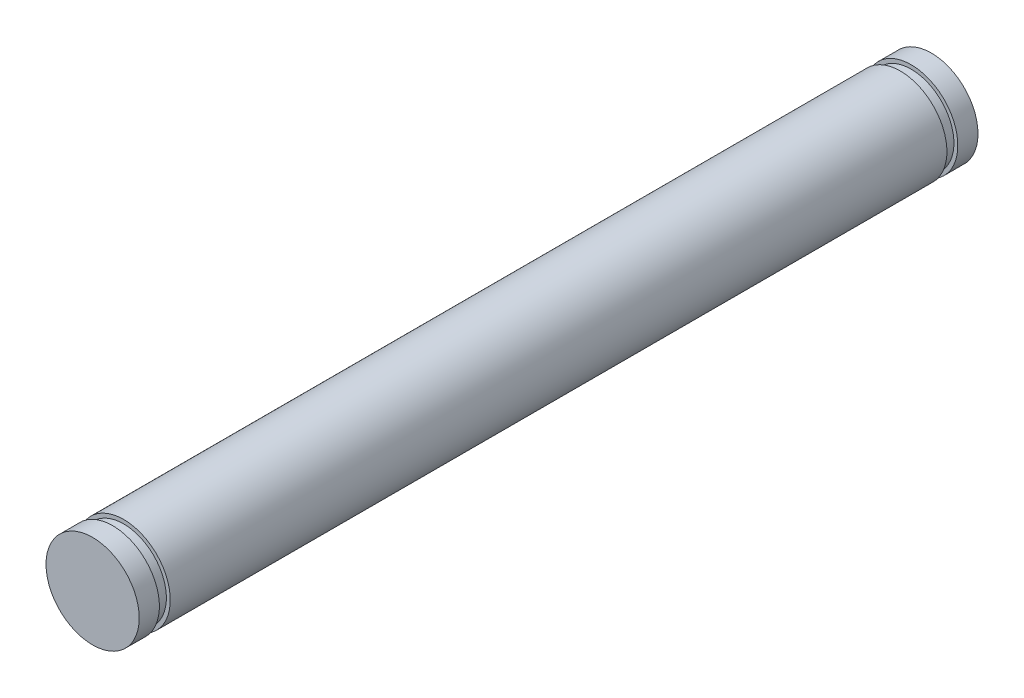
SolidWorks part; units mm, degrees
ref_plane "정면" through (0, 0, 0) normal (0, 0, 1) x (1, 0, 0)
ref_plane "윗면" through (0, 0, 0) normal (0, 1, 0) x (1, 0, 0)
ref_plane "우측면" through (0, 0, 0) normal (1, 0, 0) x (0, 0, -1)
sketch "스케치1" plane through (0, 0, 0) normal (0, 0, 1) x (1, 0, 0)
  circle A0 centre (0, 0) radius 3
  dimension "D1" = 6
extrude "보스-돌출1" add sketch "스케치1" along normal blind 54
ref_plane "평면1" through (0, 0, 27) normal (0, 0, -1) x (-1, 0, 0)
ref_plane "평면2" through (0, 0, 1.65) normal (0, 0, -1) x (-1, 0, 0)
sketch "스케치2" plane through (0, 0, 1.65) normal (0, 0, -1) x (-1, 0, 0)
  circle A0 centre (0, 0) radius 2.75
  circle A1 centre (0, 0) radius 3
  circle A2 centre (0, 0) radius 3
  dimension "D1" = 0
  dimension "D2" = 0.25
extrude "컷-돌출1" cut sketch "스케치2" against normal blind 0.35 and the other way blind 0.35
mirror "대칭 복사1" about plane through (0, 0, 27) normal (0, 0, -1) of "컷-돌출1"
